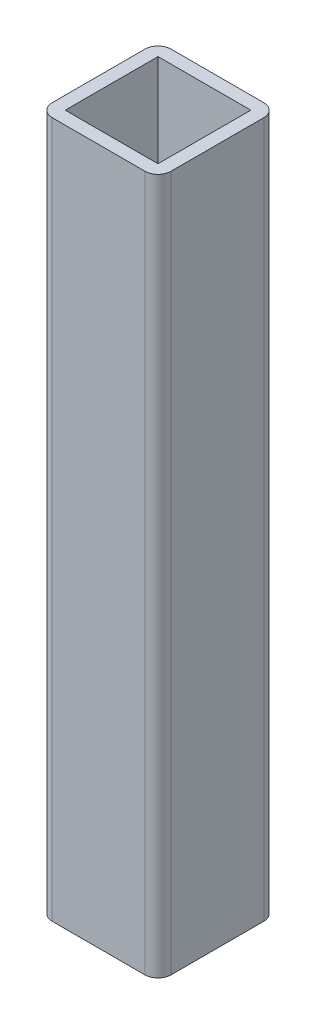
SolidWorks part; units mm, degrees
ref_plane "Front Plane" through (0, 0, 0) normal (0, 0, 1) x (1, 0, 0)
ref_plane "Top Plane" through (0, 0, 0) normal (0, 1, 0) x (1, 0, 0)
ref_plane "Right Plane" through (0, 0, 0) normal (1, 0, 0) x (0, 0, -1)
sketch "Sketch1" plane through (0, 0, 0) normal (0, 1, 0) x (1, 0, 0)
  line L1 (2.8, 0) -> (22.8, 0)
  line L2 (0, -2.8) -> (0, -22.8)
  line L3 (2.8, -25.6) -> (22.8, -25.6)
  line L4 (25.6, -2.8) -> (25.6, -22.8)
  arc A0 (22.8, 0) -> (25.6, -2.8) centre (22.8, -2.8) cw
  arc A1 (22.8, -25.6) -> (25.6, -22.8) centre (22.8, -22.8) ccw
  arc A2 (0, -22.8) -> (2.8, -25.6) centre (2.8, -22.8) ccw
  arc A3 (2.8, 0) -> (0, -2.8) centre (2.8, -2.8) ccw
  point P7 (25.6, 0)
  point P10 (25.6, -25.6)
  point P15 (0, 0)
  dimension "D2" = 2.8
  dimension "D1" = 25.6
extrude "Boss-Extrude1" add sketch "Sketch1" along normal blind 150
sketch "Sketch3" plane through (0, 0, 0) normal (0, -1, 0) x (-1, 0, 0)
  line L4 (-2.8, -2.8) -> (-22.8, -2.8)
  line L5 (-2.8, -2.8) -> (-2.8, -22.8)
  line L6 (-2.8, -22.8) -> (-22.8, -22.8)
  line L7 (-22.8, -2.8) -> (-22.8, -22.8)
  line L8 (-2.8, -2.8) -> (-22.8, -22.8) construction
  line L9 (-2.8, -22.8) -> (-22.8, -2.8) construction
  point P6 (-12.8, -12.8)
extrude "Cut-Extrude1" cut sketch "Sketch3" against normal blind 1040.5
